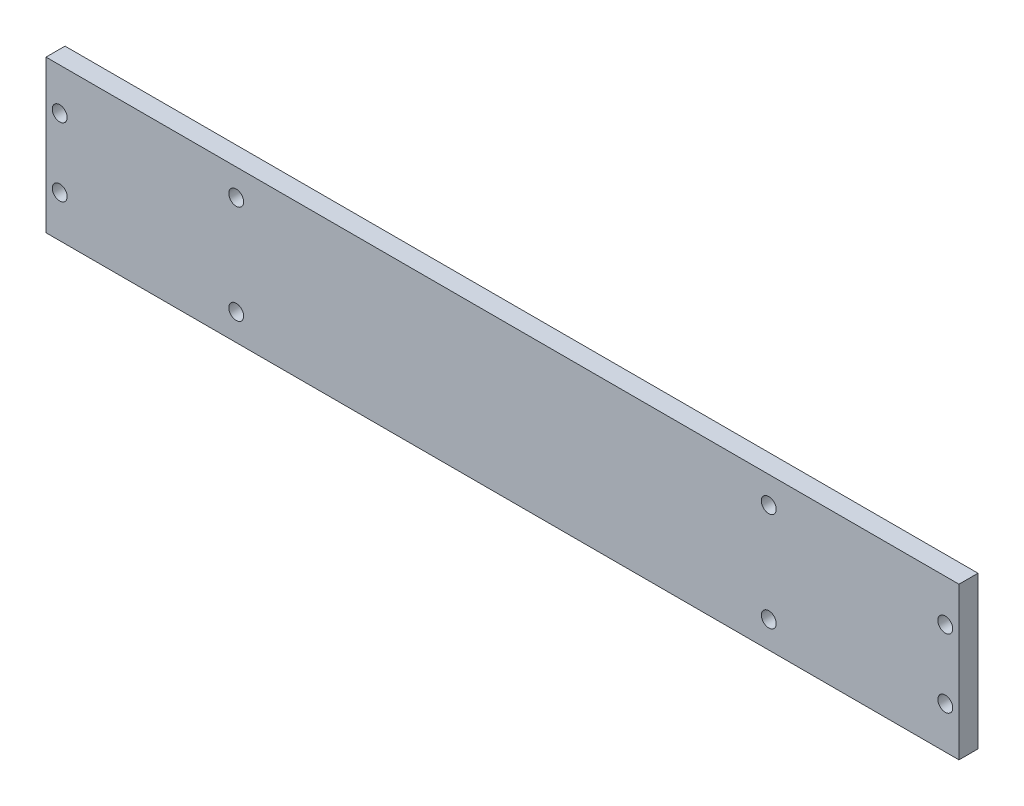
SolidWorks part; units mm, degrees
material "6061-T6 (SS)"
ref_plane "Front Plane" through (0, 0, 0) normal (0, 0, 1) x (1, 0, 0)
ref_plane "Top Plane" through (0, 0, 0) normal (0, 1, 0) x (1, 0, 0)
ref_plane "Right Plane" through (0, 0, 0) normal (1, 0, 0) x (0, 0, -1)
sketch "Sketch1" plane through (0, 0, 0) normal (0, 0, 1) x (1, 0, 0)
  line L1 (-152.4, 25.4) -> (152.4, 25.4)
  line L2 (-152.4, 25.4) -> (-152.4, -25.4)
  line L3 (-152.4, -25.4) -> (152.4, -25.4)
  line L4 (152.4, 25.4) -> (152.4, -25.4)
  line L5 (-152.4, 25.4) -> (152.4, -25.4) construction
  line L6 (-152.4, -25.4) -> (152.4, 25.4) construction
  line L7 (-88.9, 16.51) -> (88.9, 16.51) construction
  line L8 (-88.9, 16.51) -> (-88.9, -16.51) construction
  line L9 (-88.9, -16.51) -> (88.9, -16.51) construction
  line L10 (88.9, 16.51) -> (88.9, -16.51) construction
  line L11 (-88.9, 16.51) -> (88.9, -16.51) construction
  line L12 (-88.9, -16.51) -> (88.9, 16.51) construction
  line L13 (147.828, -11.43) -> (-147.828, -11.43) construction
  line L14 (147.828, -11.43) -> (147.828, 11.43) construction
  line L15 (147.828, 11.43) -> (-147.828, 11.43) construction
  line L16 (-147.828, -11.43) -> (-147.828, 11.43) construction
  line L17 (147.828, -11.43) -> (-147.828, 11.43) construction
  line L18 (147.828, 11.43) -> (-147.828, -11.43) construction
  circle A0 centre (-88.9, 16.51) radius 2.4892
  circle A1 centre (-88.9, -16.51) radius 2.4892
  circle A2 centre (88.9, -16.51) radius 2.4892
  circle A3 centre (88.9, 16.51) radius 2.4892
  circle A4 centre (-147.828, 11.43) radius 2.4892
  circle A5 centre (-147.828, -11.43) radius 2.4892
  circle A6 centre (147.828, 11.43) radius 2.4892
  circle A7 centre (147.828, -11.43) radius 2.4892
  point P0 (0, 0)
  point P6 (0, 0)
  point P15 (0, 0)
  dimension "D5" = 4.9784
  dimension "D8" = 4.9784
  dimension "D1" = 50.8
  dimension "D2" = 304.8
  dimension "D3" = 63.5
  dimension "D4" = 33.02
  dimension "D6" = 4.572
  dimension "D7" = 13.97
extrude "Boss-Extrude1" add sketch "Sketch1" along normal blind 6.35
